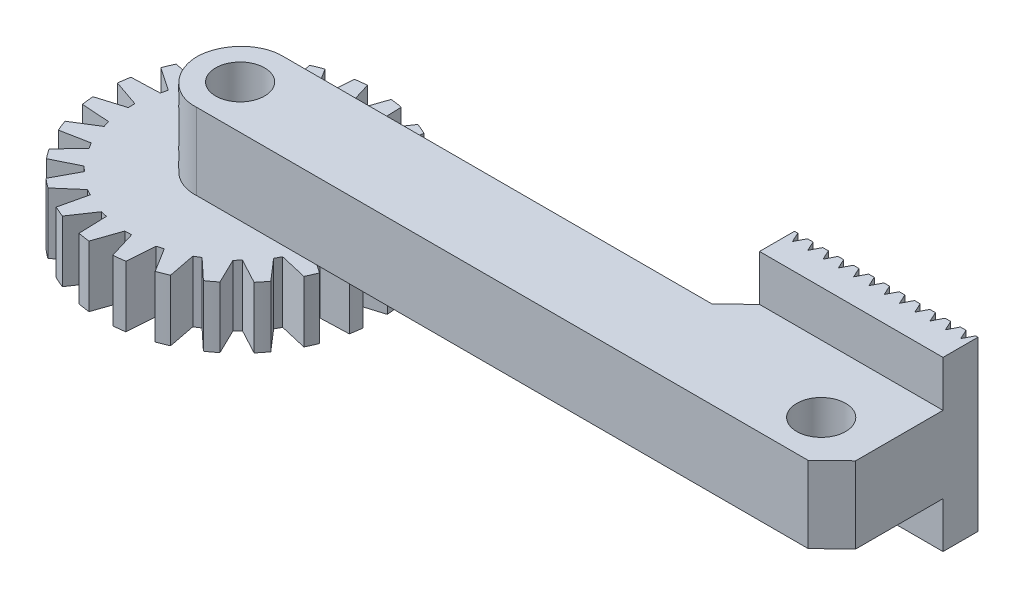
SolidWorks part; units mm, degrees
ref_plane "Plan de face" through (0, 0, 0) normal (0, 0, 1) x (1, 0, 0)
ref_plane "Plan de dessus" through (0, 0, 0) normal (0, 1, 0) x (1, 0, 0)
ref_plane "Plan de droite" through (0, 0, 0) normal (1, 0, 0) x (0, 0, -1)
sketch "Esquisse1" plane through (0, 0, 0) normal (0, 1, 0) x (1, 0, 0)
  circle A0 centre (0, 0) radius 9
  dimension "D1" = 18
extrude "Boss.-Extru.1" add sketch "Esquisse1" along normal blind 4
sketch "Esquisse2" plane through (0, 4, 0) normal (0, 1, 0) x (1, 0, 0)
  line L0 (0, 2.8563) -> (28, 2.8563)
  line L1 (0, -2.2) -> (0, 2.2) construction
  line L2 (-2.2, 0) -> (2.2, 0) construction
  line L3 (0, -2.8563) -> (28, -2.8563)
  line L25 (28, -2.8563) -> (40, -2.8563)
  line L26 (28, 2.8563) -> (29.5825, 4.3846)
  line L27 (29.5825, 4.3846) -> (29.5825, 6.6719)
  line L28 (29.5825, 6.6719) -> (41.5825, 6.6719)
  line L29 (40, -2.8563) -> (41.5825, -1.3281)
  line L30 (41.5825, 6.6719) -> (41.5825, -1.3281)
  circle A0 centre (0, 0) radius 2.8441 construction
  spline S0 degree 3 poles (0, 2.8563) (-1.6066, 2.918) (-4.1093, 0.0121) (-1.5513, -2.9527) (0, -2.8563) knots 0 0 0 0 0.499551 1 1 1 1
  dimension "D1" = 5.7126
  dimension "D2" = 28
  dimension "D3" = 12
  dimension "D4" = 2.2
  dimension "D5" = 136
  dimension "D6" = 8
  dimension "D7" = 12
extrude "Boss.-Extru.2" add sketch "Esquisse2" along normal blind 5
sketch "Esquisse3" plane through (0, 9, 0) normal (0, 1, 0) x (1, 0, 0)
  circle A0 centre (0, 0) radius 1.6
  dimension "D1" = 3.2
extrude "Enlèv. mat.-Extru.1" cut sketch "Esquisse3" against normal blind 12 and the other way blind 10
sketch "Esquisse4" plane through (0, 0, 0) normal (0, -1, 0) x (1, 0, 0)
  line L0 (-1.418, -8.8876) -> (-1.5485, -7.053)
  line L1 (-1.5485, -7.053) -> (-1.9687, -6.9288)
  line L2 (-1.9687, -6.9288) -> (-2.9487, -8.5032)
  line L3 (-1.418, -8.8876) -> (-2.361, -9.0993)
  line L4 (-2.361, -9.0993) -> (-2.9487, -8.5032)
  line L5 (-3.6699, -8.2178) -> (-3.3212, -6.4118)
  line L6 (-3.3212, -6.4118) -> (-3.6949, -6.1832)
  line L7 (-3.6949, -6.1832) -> (-5.049, -7.4503)
  line L8 (-3.6699, -8.2178) -> (-4.6357, -8.1782)
  line L9 (-4.6357, -8.1782) -> (-5.049, -7.4503)
  line L10 (-5.6718, -6.9879) -> (-4.8676, -5.3338)
  line L11 (-4.8676, -5.3338) -> (-5.1694, -5.0162)
  line L12 (-5.1694, -5.0162) -> (-6.8053, -5.8897)
  line L13 (-5.6718, -6.9879) -> (-6.5944, -6.6997)
  line L14 (-6.5944, -6.6997) -> (-6.8053, -5.8897)
  line L15 (-7.2871, -5.2818) -> (-6.0822, -3.8922)
  line L16 (-6.0822, -3.8922) -> (-6.2915, -3.5073)
  line L17 (-6.2915, -3.5073) -> (-8.0977, -3.9277)
  line L18 (-7.2871, -5.2818) -> (-8.1037, -4.7647)
  line L19 (-8.1037, -4.7647) -> (-8.0977, -3.9277)
  line L20 (-8.4059, -3.2158) -> (-6.8823, -2.1854)
  line L21 (-6.8823, -2.1854) -> (-6.9849, -1.7595)
  line L22 (-6.9849, -1.7595) -> (-8.8384, -1.698)
  line L23 (-8.4059, -3.2158) -> (-9.0607, -2.5049)
  line L24 (-9.0607, -2.5049) -> (-8.8384, -1.698)
  line L25 (-8.9518, -0.9306) -> (-7.2134, -0.3297)
  line L26 (-7.2134, -0.3297) -> (-7.2023, 0.1083)
  line L27 (-7.2023, 0.1083) -> (-8.9767, 0.6474)
  line L28 (-8.9518, -0.9306) -> (-9.4003, -0.0745)
  line L29 (-9.4003, -0.0745) -> (-8.9767, 0.6474)
  line L30 (-8.8876, 1.418) -> (-7.053, 1.5485)
  line L31 (-7.053, 1.5485) -> (-6.9288, 1.9687)
  line L32 (-6.9288, 1.9687) -> (-8.5032, 2.9487)
  line L33 (-8.8876, 1.418) -> (-9.0993, 2.361)
  line L34 (-9.0993, 2.361) -> (-8.5032, 2.9487)
  line L35 (-8.2178, 3.6699) -> (-6.4118, 3.3212)
  line L36 (-6.4118, 3.3212) -> (-6.1832, 3.6949)
  line L37 (-6.1832, 3.6949) -> (-7.4503, 5.049)
  line L38 (-8.2178, 3.6699) -> (-8.1782, 4.6357)
  line L39 (-8.1782, 4.6357) -> (-7.4503, 5.049)
  line L40 (-6.9879, 5.6718) -> (-5.3338, 4.8676)
  line L41 (-5.3338, 4.8676) -> (-5.0162, 5.1694)
  line L42 (-5.0162, 5.1694) -> (-5.8897, 6.8053)
  line L43 (-6.9879, 5.6718) -> (-6.6997, 6.5944)
  line L44 (-6.6997, 6.5944) -> (-5.8897, 6.8053)
  line L45 (-5.2818, 7.2871) -> (-3.8922, 6.0822)
  line L46 (-3.8922, 6.0822) -> (-3.5073, 6.2915)
  line L47 (-3.5073, 6.2915) -> (-3.9277, 8.0977)
  line L48 (-5.2818, 7.2871) -> (-4.7647, 8.1037)
  line L49 (-4.7647, 8.1037) -> (-3.9277, 8.0977)
  line L50 (-3.2158, 8.4059) -> (-2.1854, 6.8823)
  line L51 (-2.1854, 6.8823) -> (-1.7595, 6.9849)
  line L52 (-1.7595, 6.9849) -> (-1.698, 8.8384)
  line L53 (-3.2158, 8.4059) -> (-2.5049, 9.0607)
  line L54 (-2.5049, 9.0607) -> (-1.698, 8.8384)
  line L55 (-0.9306, 8.9518) -> (-0.3297, 7.2134)
  line L56 (-0.3297, 7.2134) -> (0.1083, 7.2023)
  line L57 (0.1083, 7.2023) -> (0.6474, 8.9767)
  line L58 (-0.9306, 8.9518) -> (-0.0745, 9.4003)
  line L59 (-0.0745, 9.4003) -> (0.6474, 8.9767)
  line L60 (1.418, 8.8876) -> (1.5485, 7.053)
  line L61 (1.5485, 7.053) -> (1.9687, 6.9288)
  line L62 (1.9687, 6.9288) -> (2.9487, 8.5032)
  line L63 (1.418, 8.8876) -> (2.361, 9.0993)
  line L64 (2.361, 9.0993) -> (2.9487, 8.5032)
  line L65 (3.6699, 8.2178) -> (3.3212, 6.4118)
  line L66 (3.3212, 6.4118) -> (3.6949, 6.1832)
  line L67 (3.6949, 6.1832) -> (5.049, 7.4503)
  line L68 (3.6699, 8.2178) -> (4.6357, 8.1782)
  line L69 (4.6357, 8.1782) -> (5.049, 7.4503)
  line L70 (5.6718, 6.9879) -> (4.8676, 5.3338)
  line L71 (4.8676, 5.3338) -> (5.1694, 5.0162)
  line L72 (5.1694, 5.0162) -> (6.8053, 5.8897)
  line L73 (5.6718, 6.9879) -> (6.5944, 6.6997)
  line L74 (6.5944, 6.6997) -> (6.8053, 5.8897)
  line L75 (7.2871, 5.2818) -> (6.0822, 3.8922)
  line L76 (6.0822, 3.8922) -> (6.2915, 3.5073)
  line L77 (6.2915, 3.5073) -> (8.0977, 3.9277)
  line L78 (7.2871, 5.2818) -> (8.1037, 4.7647)
  line L79 (8.1037, 4.7647) -> (8.0977, 3.9277)
  line L80 (8.4059, 3.2158) -> (6.8823, 2.1854)
  line L81 (6.8823, 2.1854) -> (6.9849, 1.7595)
  line L82 (6.9849, 1.7595) -> (8.8384, 1.698)
  line L83 (8.4059, 3.2158) -> (9.0607, 2.5049)
  line L84 (9.0607, 2.5049) -> (8.8384, 1.698)
  line L85 (8.9518, 0.9306) -> (7.2134, 0.3297)
  line L86 (7.2134, 0.3297) -> (7.2023, -0.1083)
  line L87 (7.2023, -0.1083) -> (8.9767, -0.6474)
  line L88 (8.9518, 0.9306) -> (9.4003, 0.0745)
  line L89 (9.4003, 0.0745) -> (8.9767, -0.6474)
  line L90 (8.8876, -1.418) -> (7.053, -1.5485)
  line L91 (7.053, -1.5485) -> (6.9288, -1.9687)
  line L92 (6.9288, -1.9687) -> (8.5032, -2.9487)
  line L93 (8.8876, -1.418) -> (9.0993, -2.361)
  line L94 (9.0993, -2.361) -> (8.5032, -2.9487)
  line L95 (8.2178, -3.6699) -> (6.4118, -3.3212)
  line L96 (6.4118, -3.3212) -> (6.1832, -3.6949)
  line L97 (6.1832, -3.6949) -> (7.4503, -5.049)
  line L98 (8.2178, -3.6699) -> (8.1782, -4.6357)
  line L99 (8.1782, -4.6357) -> (7.4503, -5.049)
  line L100 (6.9879, -5.6718) -> (5.3338, -4.8676)
  line L101 (5.3338, -4.8676) -> (5.0162, -5.1694)
  line L102 (5.0162, -5.1694) -> (5.8897, -6.8053)
  line L103 (6.9879, -5.6718) -> (6.6997, -6.5944)
  line L104 (6.6997, -6.5944) -> (5.8897, -6.8053)
  line L105 (5.2818, -7.2871) -> (3.8922, -6.0822)
  line L106 (3.8922, -6.0822) -> (3.5073, -6.2915)
  line L107 (3.5073, -6.2915) -> (3.9277, -8.0977)
  line L108 (5.2818, -7.2871) -> (4.7647, -8.1037)
  line L109 (4.7647, -8.1037) -> (3.9277, -8.0977)
  line L110 (3.2158, -8.4059) -> (2.1854, -6.8823)
  line L111 (2.1854, -6.8823) -> (1.7595, -6.9849)
  line L112 (1.7595, -6.9849) -> (1.698, -8.8384)
  line L113 (3.2158, -8.4059) -> (2.5049, -9.0607)
  line L114 (2.5049, -9.0607) -> (1.698, -8.8384)
  line L115 (0.9306, -8.9518) -> (0.3297, -7.2134)
  line L116 (0.3297, -7.2134) -> (-0.1083, -7.2023)
  line L117 (-0.1083, -7.2023) -> (-0.6474, -8.9767)
  line L118 (0.9306, -8.9518) -> (0.0745, -9.4003)
  line L119 (0.0745, -9.4003) -> (-0.6474, -8.9767)
  circle A0 centre (0, 0) radius 9 construction
  dimension "D1" = 24
extrude "Enlèv. mat.-Extru.2" cut sketch "Esquisse4" against normal blind 4
sketch "Esquisse5" plane through (0, 9, 0) normal (0, 1, 0) x (1, 0, 0)
  line L0 (41.5825, 6.6719) -> (41.5825, 4.3846)
  line L1 (41.5825, -1.3281) -> (41.5825, 6.6719) construction
  line L2 (29.5825, 4.3846) -> (29.5825, 6.6719)
  line L3 (29.5825, 6.6719) -> (41.5825, 6.6719)
  line L4 (41.5825, 4.3846) -> (29.5825, 4.3846)
extrude "Boss.-Extru.3" add sketch "Esquisse5" along normal blind 3 and the other way blind 8
sketch "Esquisse6" plane through (0, 12, 0) normal (0, 1, 0) x (1, 0, 0)
  line L0 (41.4321, 6.6719) -> (41.0974, 6.0238)
  line L1 (41.5825, 6.6719) -> (29.5825, 6.6719) construction
  line L2 (41.0974, 6.0238) -> (40.7995, 6.6719)
  line L3 (40.4321, 6.6719) -> (40.0974, 6.0238)
  line L4 (40.0974, 6.0238) -> (39.7995, 6.6719)
  line L5 (39.4321, 6.6719) -> (39.0974, 6.0238)
  line L6 (39.0974, 6.0238) -> (38.7995, 6.6719)
  line L7 (38.4321, 6.6719) -> (38.0974, 6.0238)
  line L8 (38.0974, 6.0238) -> (37.7995, 6.6719)
  line L9 (37.4321, 6.6719) -> (37.0974, 6.0238)
  line L10 (37.0974, 6.0238) -> (36.7995, 6.6719)
  line L11 (36.4321, 6.6719) -> (36.0974, 6.0238)
  line L12 (36.0974, 6.0238) -> (35.7995, 6.6719)
  line L13 (35.4321, 6.6719) -> (35.0974, 6.0238)
  line L14 (35.0974, 6.0238) -> (34.7995, 6.6719)
  line L15 (34.4321, 6.6719) -> (34.0974, 6.0238)
  line L16 (34.0974, 6.0238) -> (33.7995, 6.6719)
  line L17 (33.4321, 6.6719) -> (33.0974, 6.0238)
  line L18 (33.0974, 6.0238) -> (32.7995, 6.6719)
  line L19 (32.4321, 6.6719) -> (32.0974, 6.0238)
  line L20 (32.0974, 6.0238) -> (31.7995, 6.6719)
  line L21 (31.4321, 6.6719) -> (31.0974, 6.0238)
  line L22 (31.0974, 6.0238) -> (30.7995, 6.6719)
  line L23 (30.4321, 6.6719) -> (30.0974, 6.0238)
  line L24 (30.0974, 6.0238) -> (29.7995, 6.6719)
  line L25 (41.4321, 6.6719) -> (41.1227, 7.1286)
  line L26 (41.1227, 7.1286) -> (40.7995, 6.6719)
  line L27 (40.4321, 6.6719) -> (40.1227, 7.1286)
  line L28 (40.1227, 7.1286) -> (39.7995, 6.6719)
  line L29 (39.4321, 6.6719) -> (39.0974, 7.1659)
  line L30 (39.0974, 7.1659) -> (38.7995, 6.6719)
  line L31 (38.4321, 6.6719) -> (38.205, 7.1659)
  line L32 (38.205, 7.1659) -> (37.7995, 6.6719)
  line L33 (37.4321, 6.6719) -> (37.0974, 7.1659)
  line L34 (37.0974, 7.1659) -> (36.7995, 6.6719)
  line L35 (36.4321, 6.6719) -> (36.0974, 7.1659)
  line L36 (36.0974, 7.1659) -> (35.7995, 6.6719)
  line L37 (35.4321, 6.6719) -> (35.0974, 7.1659)
  line L38 (35.0974, 7.1659) -> (34.7995, 6.6719)
  line L39 (34.4321, 6.6719) -> (34.205, 7.1659)
  line L40 (34.205, 7.1659) -> (33.7995, 6.6719)
  line L41 (33.4321, 6.6719) -> (33.205, 7.1659)
  line L42 (33.205, 7.1659) -> (32.7995, 6.6719)
  line L43 (32.4321, 6.6719) -> (32.2093, 7.1565)
  line L44 (32.2093, 7.1565) -> (31.7995, 6.6719)
  line L45 (31.4321, 6.6719) -> (31.0974, 6.955)
  line L46 (31.0974, 6.955) -> (30.7995, 6.6719)
  line L47 (30.4321, 6.6719) -> (30.1669, 7.2487)
  line L48 (30.1669, 7.2487) -> (29.7995, 6.6719)
  dimension "D2" = 0.6326
  dimension "D3" = 0.6481
  dimension "D1" = 12
extrude "Enlèv. mat.-Extru.3" cut sketch "Esquisse6" against normal blind 11
sketch "Esquisse7" plane through (0, 9, 0) normal (0, 1, 0) x (1, 0, 0)
  line L0 (-6.6, 0) -> (6.6, 0) construction
  circle A0 centre (38, 0) radius 1.6
  dimension "D1" = 3.2
  dimension "D2" = 38
extrude "Enlèv. mat.-Extru.4" cut sketch "Esquisse7" against normal blind 11
